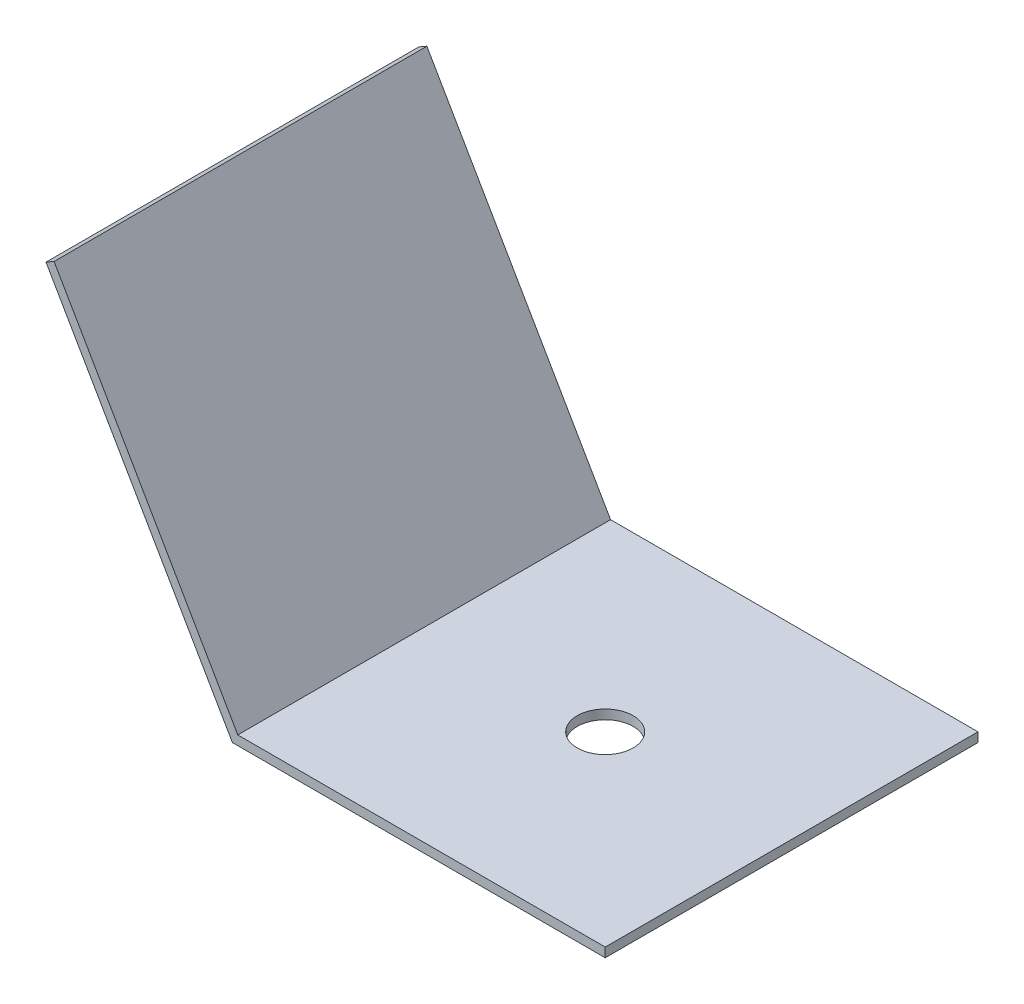
SolidWorks part; units mm, degrees
ref_plane "前视基准面" through (0, 0, 0) normal (0, 0, 1) x (1, 0, 0)
ref_plane "上视基准面" through (0, 0, 0) normal (0, 1, 0) x (1, 0, 0)
ref_plane "右视基准面" through (0, 0, 0) normal (1, 0, 0) x (0, 0, -1)
sketch "草图1" plane through (0, 0, 0) normal (0, 1, 0) x (1, 0, 0)
  line L1 (20, 20) -> (-20, 20)
  line L2 (20, 20) -> (20, -20)
  line L3 (20, -20) -> (-20, -20)
  line L4 (-20, 20) -> (-20, -20)
  line L5 (20, 20) -> (-20, -20) construction
  line L6 (20, -20) -> (-20, 20) construction
  circle A0 centre (0, 0) radius 3
  point P0 (0, 0)
  dimension "D1" = 40
  dimension "D2" = 40
extrude "凸台-拉伸3" add sketch "草图1" along normal blind 1
ref_plane "基准面2" through (-15, -8.6603, 0) normal (0.866, 0.5, 0) x (0, 0, 1)
sketch "草图3" plane through (-15, -8.6603, 0) normal (0.866, 0.5, 0) x (0, 0, 1)
  line L0 (-20, -10) -> (20, -10)
  line L1 (-20, -10) -> (20, -10) construction
  line L2 (20, -10) -> (20, -50)
  line L3 (20, -50) -> (-20, -50)
  line L4 (-20, -50) -> (-20, -10)
  dimension "D1" = 40
extrude "凸台-拉伸5" add sketch "草图3" along normal blind 1
